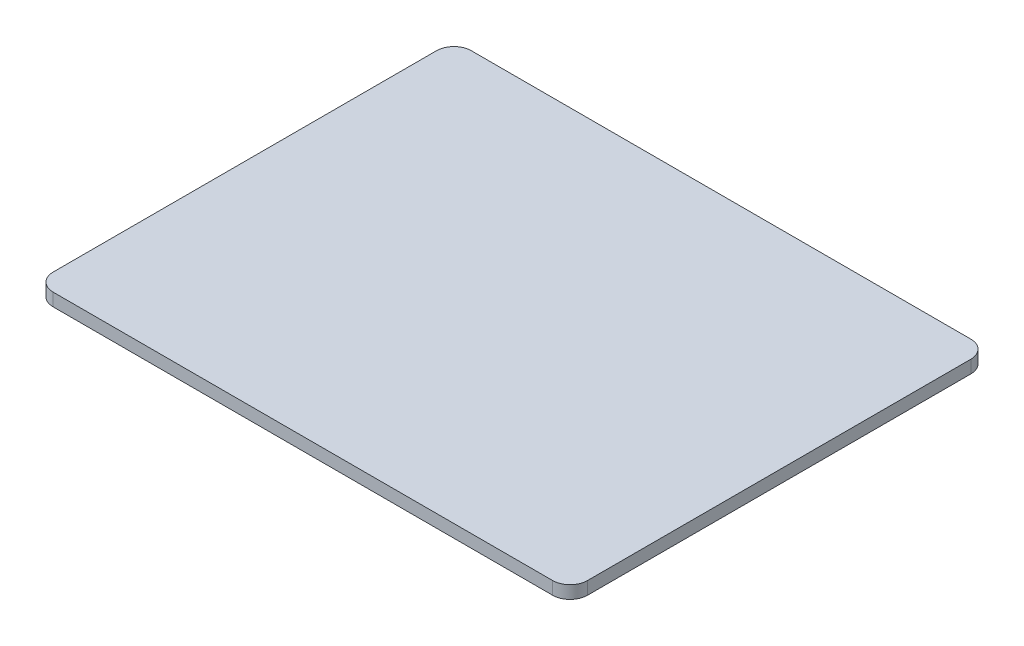
SolidWorks part; units mm, degrees
ref_plane "CL Y" through (0, 0, 0) normal (0, 0, 1) x (1, 0, 0)
ref_plane "Bottom" through (0, 0, 0) normal (0, 1, 0) x (1, 0, 0)
ref_plane "CL X" through (0, 0, 0) normal (1, 0, 0) x (0, 0, -1)
sketch "Sketch1" plane through (0, 0, 0) normal (0, 1, 0) x (1, 0, 0)
  line L0 (0, -55) -> (0, 55) construction
  line L1 (-25, 20) -> (25, 20) construction
  line L2 (-25, 20) -> (-25, -20) construction
  line L3 (-25, -20) -> (25, -20) construction
  line L4 (25, 20) -> (25, -20) construction
  line L5 (-55, 0) -> (55, 0) construction
  line L6 (-21.5, 18) -> (21.5, 18)
  line L7 (23, 16.5) -> (23, -16.5)
  line L8 (-21.5, -18) -> (21.5, -18)
  line L9 (-23, 16.5) -> (-23, -16.5)
  line L10 (-23, -18) -> (23, -18) construction
  line L11 (-23, 18) -> (-23, -18) construction
  line L12 (23, 18) -> (23, -18) construction
  line L13 (-23, 18) -> (23, 18) construction
  arc A0 (-21.5, -18) -> (-23, -16.5) centre (-21.5, -16.5) cw
  arc A1 (21.5, -18) -> (23, -16.5) centre (21.5, -16.5) ccw
  arc A2 (23, 16.5) -> (21.5, 18) centre (21.5, 16.5) ccw
  arc A3 (-23, 16.5) -> (-21.5, 18) centre (-21.5, 16.5) cw
  point P4 (0, 20)
  point P7 (25, 0)
  dimension "D4" = 1.5
  dimension "D1" = 40
  dimension "D2" = 50
  dimension "D3" = 2
extrude "Boss-Extrude1" add sketch "Sketch1" along normal blind 1.1
